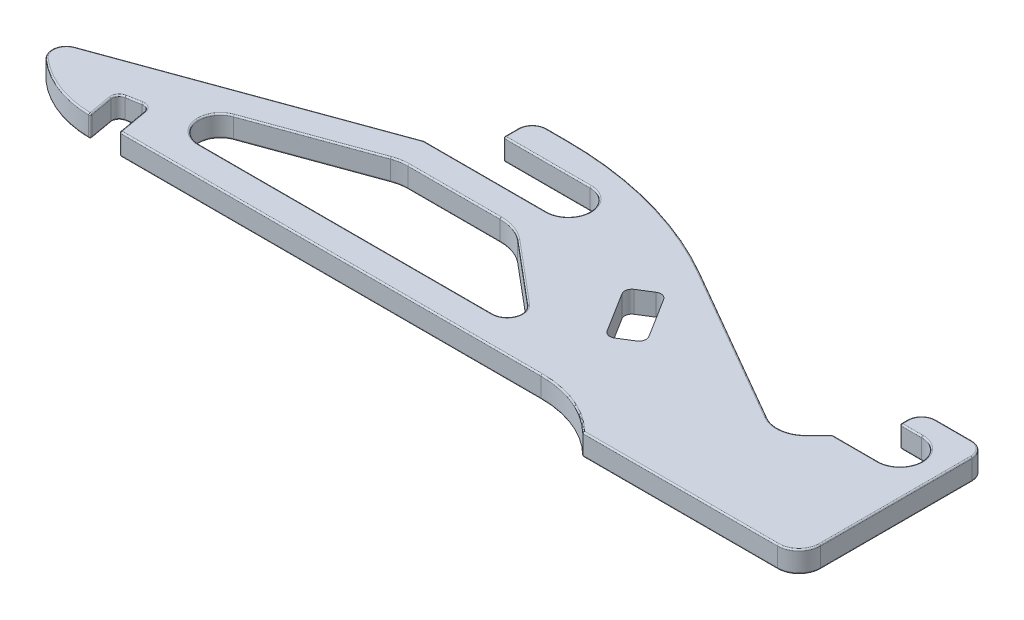
SolidWorks part; units mm, degrees
ref_plane "Front Plane" through (0, 0, 0) normal (0, 0, 1) x (1, 0, 0)
ref_plane "Top Plane" through (0, 0, 0) normal (0, 1, 0) x (1, 0, 0)
ref_plane "Right Plane" through (0, 0, 0) normal (1, 0, 0) x (0, 0, -1)
sketch "Sketch1" plane through (0, 0, 0) normal (0, 1, 0) x (1, 0, 0)
  line L0 (0, -3) -> (-17, -3)
  line L1 (-17, -3) -> (-52.5179, -15.9274)
  line L2 (0, 3) -> (-12, 3)
  line L3 (-12, 3) -> (-12, 5)
  line L4 (-10, 7) -> (-7.1103, 7)
  line L5 (53, -10) -> (46.6569, -10)
  line L6 (53, -4) -> (50, -4)
  line L7 (50, -4) -> (50, -3)
  line L8 (52, -1) -> (57, -1)
  line L9 (59, -3) -> (59, -24)
  line L10 (56, -27) -> (29, -27)
  line L11 (44.8284, -11.8284) -> (46.6569, -10)
  line L12 (40, -12.4641) -> (17.8897, 0.3013)
  line L13 (19.202, -37) -> (19.202, -23) construction
  line L14 (19.202, -23) -> (-39.2383, -23)
  line L15 (-2.4785, -7) -> (-15.2367, -7)
  line L16 (-17.2889, -7.3618) -> (-33.2766, -13.1809)
  line L17 (-32.2506, -19) -> (8.5114, -19)
  line L18 (1.3782, -8.4037) -> (9.797, -15.4679)
  line L19 (-43.3, -23) -> (-43.9078, -19.5532)
  line L20 (-43.0966, -18.3947) -> (-41.127, -18.0474)
  line L21 (-39.9685, -18.8586) -> (-39.2383, -23)
  line L22 (15.1122, -7.6726) -> (18.5567, -13.1849)
  line L23 (19.9346, -13.503) -> (21.8003, -12.3372)
  line L24 (22.1185, -10.9592) -> (18.674, -5.4469)
  line L25 (17.296, -5.1288) -> (15.4303, -6.2946)
  line L26 (0, 0) -> (16.955, -27.1336) construction
  arc A0 (0, -3) -> (0, 3) centre (0, 0) ccw
  arc A1 (53, -10) -> (53, -4) centre (53, -7) ccw
  arc A2 (40, -12.4641) -> (44.8284, -11.8284) centre (42, -9) ccw
  arc A3 (50, -3) -> (52, -1) centre (52, -3) cw
  arc A4 (17.8897, 0.3013) -> (-7.1103, 7) centre (-7.1103, -43) ccw
  arc A5 (29, -27) -> (19.202, -23) centre (19.202, -37) ccw
  arc A6 (-53.1467, -19.3156) -> (-52.5179, -15.9274) centre (-51.8338, -17.8068) cw
  arc A7 (8.5114, -19) -> (9.797, -15.4679) centre (8.5114, -17) ccw
  arc A8 (-32.2506, -19) -> (-33.2766, -13.1809) centre (-32.2506, -16) cw
  arc A9 (-2.4785, -7) -> (1.3782, -8.4037) centre (-2.4785, -13) cw
  arc A10 (-15.2367, -7) -> (-17.2889, -7.3618) centre (-15.2367, -13) ccw
  arc A11 (59, -24) -> (56, -27) centre (56, -24) cw
  arc A12 (57, -1) -> (59, -3) centre (57, -3) cw
  arc A13 (-12, 5) -> (-10, 7) centre (-10, 5) cw
  arc A14 (-53.1467, -19.3156) -> (-43.3, -23) centre (-43.3, -8) ccw
  arc A15 (-41.127, -18.0474) -> (-39.9685, -18.8586) centre (-40.9533, -19.0322) cw
  arc A16 (-43.9078, -19.5532) -> (-43.0966, -18.3947) centre (-42.923, -19.3795) cw
  arc A17 (18.5567, -13.1849) -> (19.9346, -13.503) centre (19.4047, -12.655) ccw
  arc A18 (21.8003, -12.3372) -> (22.1185, -10.9592) centre (21.2704, -11.4892) ccw
  arc A19 (18.674, -5.4469) -> (17.296, -5.1288) centre (17.8259, -5.9768) ccw
  arc A20 (15.4303, -6.2946) -> (15.1122, -7.6726) centre (15.9602, -7.1427) ccw
  point P24 (50, -1)
  point P41 (-0.2947, -7)
  point P44 (-16.2947, -7)
  point P47 (59, -27)
  point P50 (59, -1)
  point P53 (-12, 7)
  point P62 (-44.0814, -18.5684)
  point P72 (22.6484, -11.8073)
  point P75 (18.1441, -4.5989)
  point P78 (14.5823, -6.8245)
  dimension "D1" = 6
  dimension "D5" = 6
  dimension "D10" = 18
  dimension "D11" = 8
  dimension "D15" = 2
  dimension "D19" = 50
  dimension "D20" = 28
  dimension "D23" = 15
  dimension "D27" = 40
  dimension "D28" = 2
  dimension "D29" = 6
  dimension "D30" = 3
  dimension "D31" = 2
  dimension "D32" = 2
  dimension "D37" = 3
  dimension "D38" = 30
  dimension "D39" = 2
  dimension "D40" = 1
  dimension "D46" = 1
  dimension "D2" = 12
  dimension "D3" = 17
  dimension "D4" = 20
  dimension "D6" = 3
  dimension "D7" = 6
  dimension "D8" = 4
  dimension "D9" = 30
  dimension "D12" = 17
  dimension "D13" = 9
  dimension "D14" = 26
  dimension "D16" = 30
  dimension "D17" = 53
  dimension "D18" = 4
  dimension "D21" = 20
  dimension "D22" = 10
  dimension "D24" = 4
  dimension "D25" = 4
  dimension "D26" = 16
  dimension "D33" = 4
  dimension "D34" = 100
  dimension "D35" = 43.3
  dimension "D36" = 4.5
  dimension "D41" = 58
  dimension "D42" = 4.2
  dimension "D43" = 8.5
  dimension "D44" = 8.75
  dimension "D45" = 16.25
  dimension "D47" = 45
extrude "Boss-Extrude1" add sketch "Sketch1" along normal blind 3
fillet "Fillet1" radius 0.2 80 edges at (-6, 0, -3) (3, 0, 0) (-12, 0, -4) (-11.4142, 0, -6.4142) (-8.5551, 0, -7) (5.8307, 0, -5.2963) (28.9449, 0, 6.0814) (42.5221, 0, 12.9658) (51.5, 0, 4) (56, 0, 7) (-0.4264, 0, 7.3618) (-8.8576, 0, 7) (-16.2786, 0, 7.0912) (-25.2827, 0, 10.2714) (-35.205, 0, 16.5209) (-11.8696, 0, 19) (10.3908, 0, 17.684) (50, 0, 3.5) (50.5858, 0, 1.5858) (54.5, 0, 1) (58.4142, 0, 1.5858) (59, 0, 13.5) (58.1213, 0, 26.1213) (24.4935, 0, 24.0385) (-34.7589, 0, 9.4637) (-53.8002, 0, 17.4419) (-39.6034, 0, 20.9293) (-40.3798, 0, 18.2131) (-42.1118, 0, 18.2211) (-43.7421, 0, 18.8059) (-39.6034, 3, 20.9293) (-40.3798, 3, 18.2131) (-42.1118, 3, 18.2211) (-43.7421, 3, 18.8059) (-11.8696, 3, 19) (10.3908, 3, 17.684) (5.5876, 3, 11.9358) (-0.4264, 3, 7.3618) (-8.8576, 3, 7) (-16.2786, 3, 7.0912) (-25.2827, 3, 10.2714) (49.8284, 3, 10) (56, 3, 7) (-6, 3, -3) (3, 3, 0) (-48.5567, 3, 22.0487) (-53.8002, 3, 17.4419) (45.7426, 3, 10.9142) (42.5221, 3, 12.9658) (-12, 3, -4) (-11.4142, 3, -6.4142) (-8.5551, 3, -7) (5.8307, 3, -5.2963) (-10.0181, 3, 23) (50, 3, 3.5) (50.5858, 3, 1.5858) (54.5, 3, 1) (58.4142, 3, 1.5858) (42.5, 3, 27) (58.1213, 3, 26.1213) (-8.5, 0, 3) (45.7426, 0, 10.9142) (49.8284, 0, 10) (5.5876, 0, 11.9358) (42.5, 0, 27) (50, 1.5, 4) (-12, 1.5, -3) (-39.2383, 1.5, 23) (-43.3, 1.5, 23) (-10.0181, 0, 23) (-48.5567, 0, 22.0487) (-43.6039, 0, 21.2766) (-43.6039, 3, 21.2766) (-35.205, 3, 16.5209) (51.5, 3, 4) (-8.5, 3, 3) (-34.7589, 3, 9.4637) (28.9449, 3, 6.0814) (24.4935, 3, 24.0385) (59, 3, 13.5)
